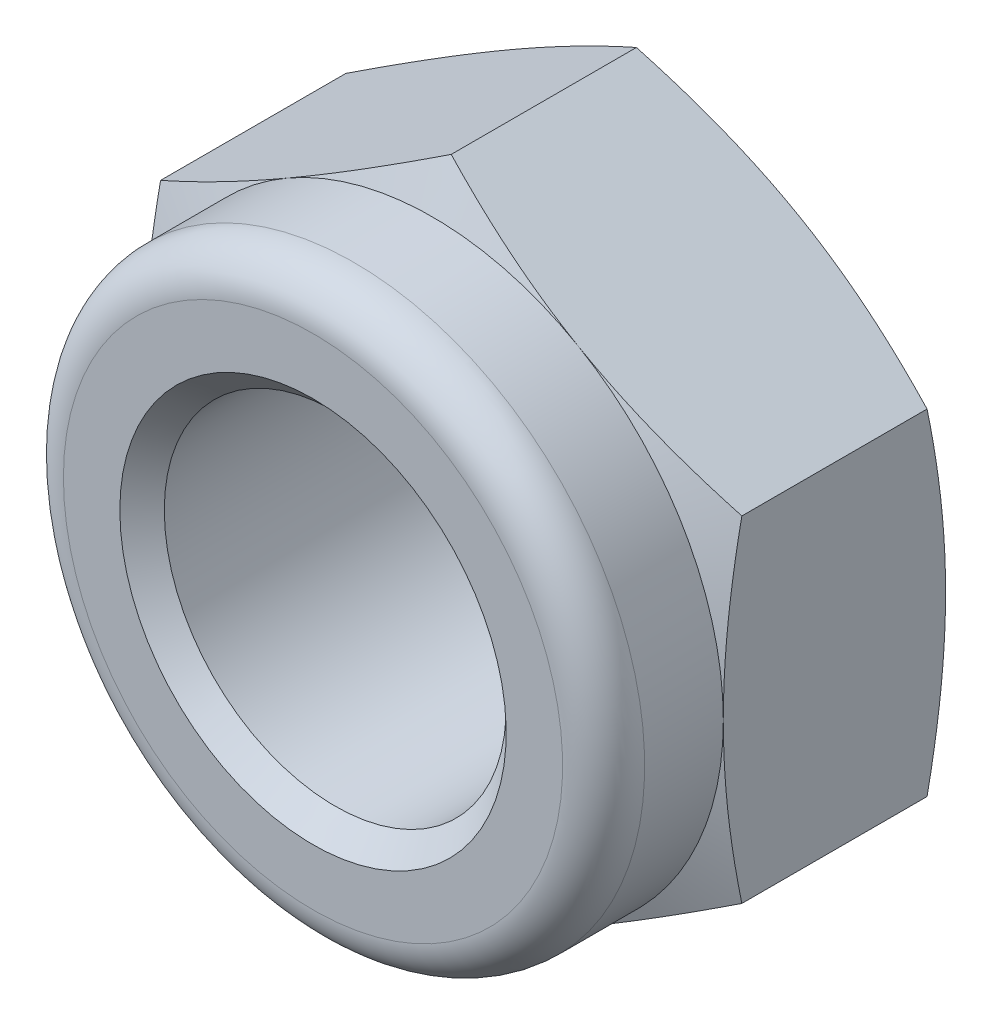
SolidWorks part; units mm, degrees
material "Plain Carbon Steel"
ref_plane "Front Plane" through (0, 0, 0) normal (0, 0, 1) x (1, 0, 0)
ref_plane "Top Plane" through (0, 0, 0) normal (0, 1, 0) x (1, 0, 0)
ref_plane "Right Plane" through (0, 0, 0) normal (1, 0, 0) x (0, 0, -1)
sketch "Sketch1" plane through (0, 0, 0) normal (0, 0, 1) x (1, 0, 0)
  line L1 (0, -9.815) -> (8.5, -4.9075)
  line L2 (8.5, -4.9075) -> (8.5, 4.9075)
  line L3 (8.5, 4.9075) -> (0, 9.815)
  line L4 (0, 9.815) -> (-8.5, 4.9075)
  line L5 (-8.5, 4.9075) -> (-8.5, -4.9075)
  line L6 (-8.5, -4.9075) -> (0, -9.815)
  circle A0 centre (0, 0) radius 8.5 construction
  circle A1 centre (0, 0) radius 5
  dimension "D2" = 10
  dimension "D1" = 17
extrude "Boss-Extrude1" add sketch "Sketch1" along normal blind 6.5
sketch "Sketch3" plane through (0, 0, 0) normal (0, 1, 0) x (0, 0, -1)
  line L0 (-6.5, 8.5) -> (-8.8, 8.5)
  line L1 (-6.5, -8.5) -> (-6.5, 0) construction
  line L2 (-10, 7.3) -> (-10, 5)
  line L3 (-10, 5) -> (-6.5, 5)
  line L5 (-6.5, 5) -> (-6.5, 8.5)
  line L6 (0, 0) -> (-2.4, 0) construction
  arc A0 (-8.8, 8.5) -> (-10, 7.3) centre (-8.8, 7.3) ccw
  dimension "D1" = 1.2
  dimension "D2" = 10
revolve "Revolve1" add sketch "Sketch3" angle 360 about L6
sketch "Sketch2" plane through (0, 0, 0) normal (1, 0, 0) x (0, 0, -1)
  line L0 (-6.5, 9.815) -> (-6.5, 8.5)
  line L1 (-6.5, 4.9075) -> (-6.5, 7.3612) construction
  line L2 (-6.5, 8.5) -> (-5.9583, 9.815)
  line L3 (-6.5, 9.815) -> (0, 9.815) construction
  line L4 (-5.9583, 9.815) -> (-6.5, 9.815)
  line L5 (-0.5417, 9.815) -> (0, 9.815)
  line L6 (0, 9.815) -> (0, 8.5)
  line L7 (0, 4.9075) -> (0, 9.815) construction
  line L8 (0, 8.5) -> (-0.5417, 9.815)
  line L9 (-5.9583, 9.815) -> (-5.4167, 9.815) construction
  line L10 (-5.4167, 9.815) -> (-4.875, 9.815) construction
  line L11 (-4.875, 9.815) -> (-4.3333, 9.815) construction
  line L12 (-4.3333, 9.815) -> (-3.7917, 9.815) construction
  line L13 (-3.7917, 9.815) -> (-3.25, 9.815) construction
  line L14 (-3.25, 9.815) -> (-2.7083, 9.815) construction
  line L15 (-2.7083, 9.815) -> (-2.1667, 9.815) construction
  line L16 (-2.1667, 9.815) -> (-1.625, 9.815) construction
  line L17 (-1.625, 9.815) -> (-1.0833, 9.815) construction
  line L18 (0, 0) -> (-2.4, 0) construction
  line L20 (-10, 5) -> (-9.35, 5)
  line L21 (-9.35, 5) -> (-10, 5.65)
  line L22 (-10, 5.65) -> (-10, 5)
  line L23 (0, 5) -> (-0.65, 5)
  line L24 (0, -4.9075) -> (0, 4.9075) construction
  line L25 (-0.65, 5) -> (0, 5.65)
  line L26 (0, 5.65) -> (0, 5)
  line L27 (-10, 7.3) -> (-10, -7.3) construction
  line L28 (-5.2, 5) -> (-5.85, 5) construction
  line L29 (-5.85, 5) -> (-6.5, 5) construction
  line L30 (-5.2, 5) -> (-4.55, 5) construction
  line L31 (-4.55, 5) -> (-3.9, 5) construction
  line L32 (-3.9, 5) -> (-3.25, 5) construction
  line L33 (-3.25, 5) -> (-2.6, 5) construction
  line L34 (-2.6, 5) -> (-1.95, 5) construction
  line L35 (-1.95, 5) -> (-1.3, 5) construction
  line L36 (-1.3, 5) -> (-0.65, 5) construction
  line L37 (-1.0833, 9.815) -> (-0.5417, 9.815) construction
  line L38 (-6.5, 0) -> (-6.5, 4.9075) construction
  dimension "D1" = 17
revolve "Cut-Revolve1" cut sketch "Sketch2" angle 360 about L18
